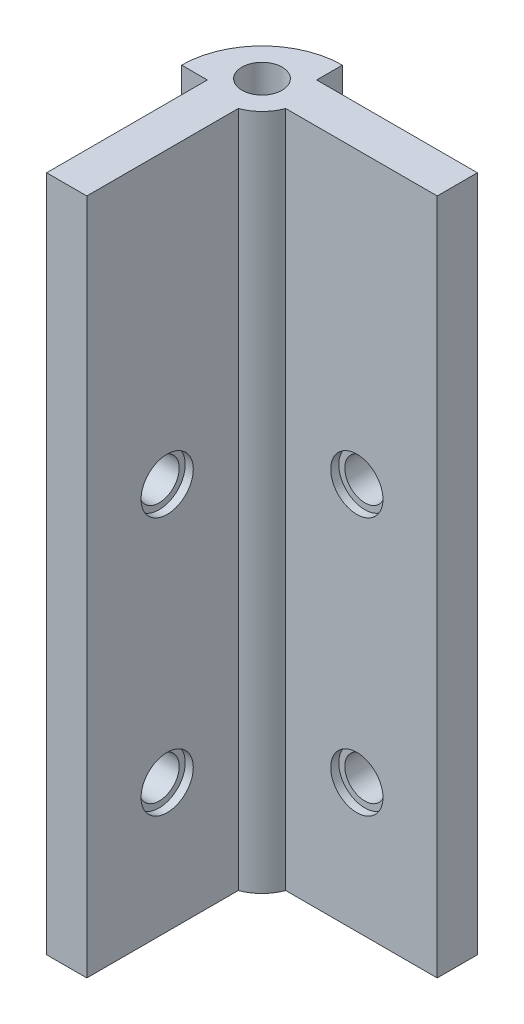
SolidWorks part; units mm, degrees
material "ABS"
ref_plane "Front Plane" through (0, 0, 0) normal (0, 0, 1) x (1, 0, 0)
ref_plane "Top Plane" through (0, 0, 0) normal (0, 1, 0) x (1, 0, 0)
ref_plane "Right Plane" through (0, 0, 0) normal (1, 0, 0) x (0, 0, -1)
sketch "Sketch4" plane through (0, 0, 0) normal (0, 1, 0) x (1, 0, 0)
  line L1 (-16.4403, 12.5012) -> (-16.4403, -277.4988) construction
  line L12 (-5.2868, 14.3012) -> (13.5597, 14.3012)
  line L35 (-8.2403, 11.3476) -> (-8.2403, -7.4988)
  line L36 (148.5597, 22.5012) -> (-6.4403, 22.5012) construction
  line L42 (-16.4403, 22.5012) -> (-13.5114, 19.5722) construction
  line L44 (-16.4403, 12.5012) -> (-13.2403, 12.5012)
  line L45 (-13.2403, 12.5012) -> (-13.2403, -7.4988)
  line L46 (-13.2403, -7.4988) -> (-8.2403, -7.4988)
  line L47 (-13.5114, 19.5722) -> (-11.7436, 17.8045) construction
  line L49 (-11.7436, 17.8045) -> (-9.9759, 16.0367) construction
  line L51 (-6.4403, 22.5012) -> (-6.4403, 19.3012)
  line L52 (-6.4403, 19.3012) -> (13.5597, 19.3012)
  line L53 (13.5597, 19.3012) -> (13.5597, 14.3012)
  line L54 (-6.2403, 19.5012) -> (148.3597, 19.5012) construction
  line L55 (-9.9759, 16.0367) -> (-8.2081, 14.2689) construction
  line L56 (-8.2081, 14.2689) -> (-6.4403, 12.5012) construction
  line L60 (-16.4403, 22.5012) -> (-16.4403, 12.5012) construction
  line L61 (-16.4403, 22.5012) -> (-6.4403, 22.5012) construction
  line L62 (-9.9759, 16.0367) -> (-4.9759, 16.0367) construction
  line L63 (-9.9759, 11.0367) -> (-9.9759, 16.0367) construction
  arc A2 (-6.4403, 22.5012) -> (-16.4403, 12.5012) centre (-6.4403, 12.5012) ccw
  circle A8 centre (-9.9759, 16.0367) radius 2.5
  arc A13 (-4.9759, 16.0367) -> (-9.9759, 11.0367) centre (-9.9759, 16.0367) cw construction
  arc A16 (-5.2868, 14.3012) -> (-8.2403, 11.3476) centre (-9.9759, 16.0367) cw
  arc A17 (-6.4403, 22.5012) -> (-16.4403, 12.5012) centre (-6.4403, 12.5012) ccw construction
  dimension "D6" = 2.5
  dimension "D7" = 5
  dimension "D1" = 5
  dimension "D5" = 0.2
  dimension "D8" = 20
  dimension "D9" = 2.5
extrude "Boss-Extrude1" add sketch "Sketch4" along normal blind 64.27
sketch "Sketch5" plane through (0, 0, -19.3012) normal (0, 0, -1) x (-1, 0, 0)
  line L0 (6.4403, 64.27) -> (-13.5597, 64.27) construction
  line L1 (-3.5597, 64.27) -> (-3.5597, 48.2025) construction
  line L2 (-3.5597, 48.2025) -> (-3.5597, 32.135) construction
  line L3 (-3.5597, 32.135) -> (-3.5597, 16.0675) construction
  line L4 (-3.5597, 16.0675) -> (-3.5597, 0) construction
  line L5 (-13.5597, 0) -> (6.4403, 0) construction
  circle A10 centre (-3.5597, 48.2025) radius 2.5
  circle A12 centre (-3.5597, 16.0675) radius 2.5
  point P2 (-3.5597, 64.27)
  dimension "D1" = 5
extrude "Cut-Extrude1" cut sketch "Sketch5" against normal through all
sketch "Sketch6" plane through (-13.2403, 0, 0) normal (-1, 0, 0) x (0, 0, 1)
  line L0 (7.4988, 64.27) -> (-12.5012, 64.27) construction
  line L1 (-2.5012, 64.27) -> (-2.5012, 48.2025) construction
  line L2 (-2.5012, 16.0675) -> (-2.5012, 32.135) construction
  line L3 (-2.5012, 16.0675) -> (-2.5012, 0) construction
  line L4 (-12.5012, 0) -> (7.4988, 0) construction
  line L5 (-2.5012, 32.135) -> (-2.5012, 48.2025) construction
  circle A0 centre (-2.5012, 48.2025) radius 2.5
  circle A2 centre (-2.5012, 16.0675) radius 2.5
  point P2 (-2.5012, 64.27)
  dimension "D1" = 5
extrude "Cut-Extrude2" cut sketch "Sketch6" against normal through all
sketch "Sketch7" plane through (-8.2403, 0, 0) normal (1, 0, 0) x (0, 0, -1)
  circle A0 centre (2.5012, 48.2025) radius 3.25
  circle A1 centre (2.5012, 16.0675) radius 3.25
  circle A2 centre (2.5012, 48.2025) radius 2.5 construction
  circle A3 centre (2.5012, 16.0675) radius 2.5 construction
  dimension "D1" = 6.5
extrude "Cut-Extrude3" cut sketch "Sketch7" against normal blind 1
sketch "Sketch8" plane through (0, 0, -14.3012) normal (0, 0, 1) x (1, 0, 0)
  circle A0 centre (3.5597, 48.2025) radius 3.25
  circle A1 centre (3.5597, 16.0675) radius 3.25
  circle A2 centre (3.5597, 48.2025) radius 2.5 construction
  circle A3 centre (3.5597, 16.0675) radius 2.5 construction
  dimension "D1" = 6.5
extrude "Cut-Extrude4" cut sketch "Sketch8" against normal blind 1
sketch "Sketch9" plane through (0, 64.27, 0) normal (0, 1, 0) x (1, 0, 0)
  line L0 (-6.4403, 22.5012) -> (-6.4403, 19.3012)
  line L1 (-6.4403, 19.3012) -> (13.5597, 19.3012)
  line L2 (13.5597, 19.3012) -> (13.5597, 14.3012)
  line L3 (13.5597, 14.3012) -> (-5.2868, 14.3012)
  line L4 (-8.2403, 11.3476) -> (-8.2403, -7.4988)
  line L5 (-8.2403, -7.4988) -> (-13.2403, -7.4988)
  line L6 (-13.2403, -7.4988) -> (-13.2403, 12.5012)
  line L7 (-13.2403, 12.5012) -> (-16.4403, 12.5012)
  arc A0 (-16.4403, 12.5012) -> (-6.4403, 22.5012) centre (-6.4403, 12.5012) cw
  arc A1 (-5.2868, 14.3012) -> (-8.2403, 11.3476) centre (-9.9759, 16.0367) cw
  circle A2 centre (-9.9759, 16.0367) radius 2.5
extrude "Boss-Extrude2" add sketch "Sketch9" along normal blind 20
equation "\"tolerance\"= 0.1mm"
